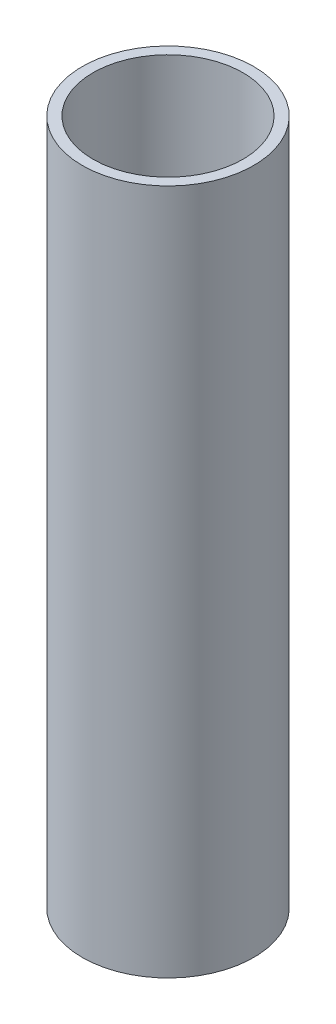
SolidWorks part; units mm, degrees
material "6061-T6 (SS)"
ref_plane "Front Plane" through (0, 0, 0) normal (0, 0, 1) x (1, 0, 0)
ref_plane "Top Plane" through (0, 0, 0) normal (0, 1, 0) x (1, 0, 0)
ref_plane "Right Plane" through (0, 0, 0) normal (1, 0, 0) x (0, 0, -1)
sketch "Sketch1" plane through (0, 0, 0) normal (0, 1, 0) x (1, 0, 0)
  circle A0 centre (0, 0) radius 25.4
  circle A1 centre (0, 0) radius 22.225
  dimension "D1" = 50.8
  dimension "D2" = 3.175
extrude "Boss-Extrude1" add sketch "Sketch1" along normal blind 203.2
